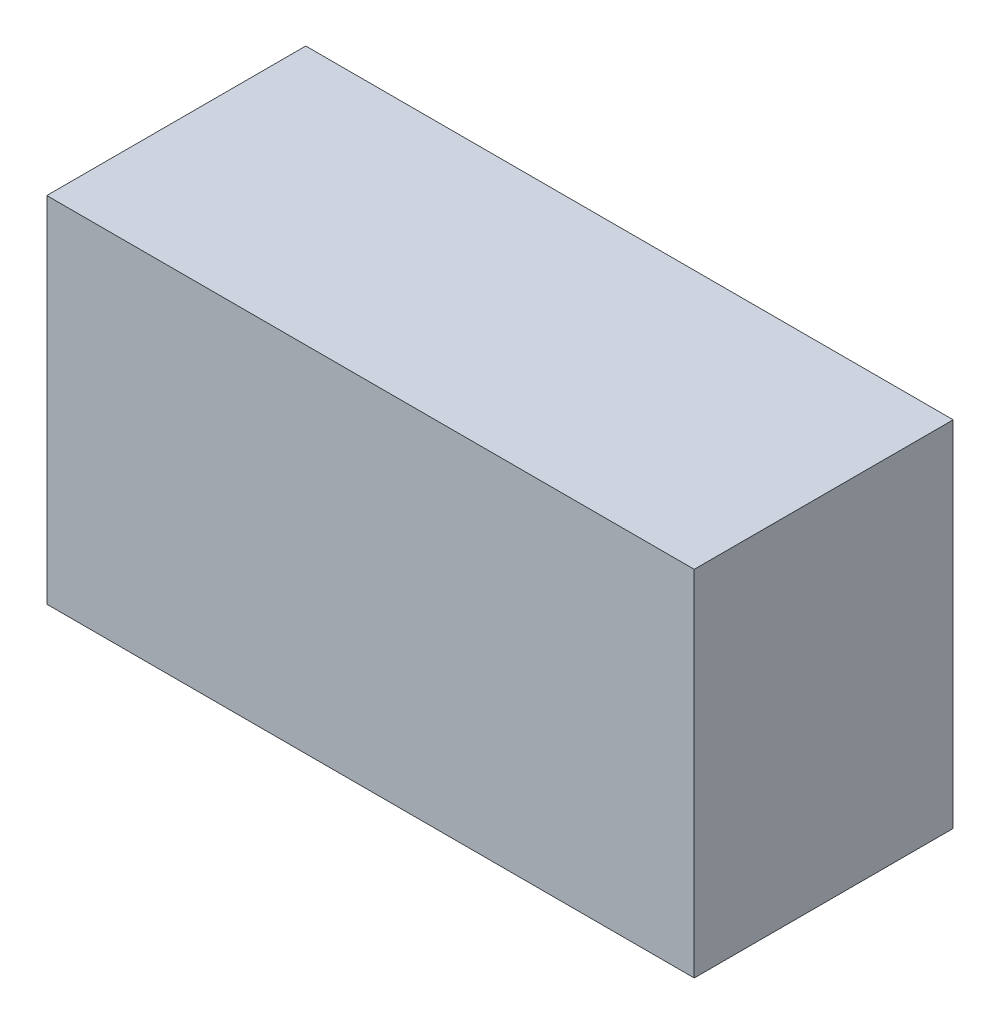
SolidWorks part; units mm, degrees
ref_plane "Front Plane" through (0, 0, 0) normal (0, 0, 1) x (1, 0, 0)
ref_plane "Top Plane" through (0, 0, 0) normal (0, 1, 0) x (1, 0, 0)
ref_plane "Right Plane" through (0, 0, 0) normal (1, 0, 0) x (0, 0, -1)
sketch "Sketch1" plane through (0, 0, 0) normal (0, 0, 1) x (1, 0, 0)
  line L1 (37.5, -20.5) -> (-37.5, -20.5)
  line L2 (37.5, -20.5) -> (37.5, 20.5)
  line L3 (37.5, 20.5) -> (-37.5, 20.5)
  line L4 (-37.5, -20.5) -> (-37.5, 20.5)
  line L5 (37.5, -20.5) -> (-37.5, 20.5) construction
  line L6 (37.5, 20.5) -> (-37.5, -20.5) construction
  point P0 (0, 0)
  dimension "D1" = 75
  dimension "D2" = 41
extrude "Boss-Extrude1" add sketch "Sketch1" along normal blind 30
